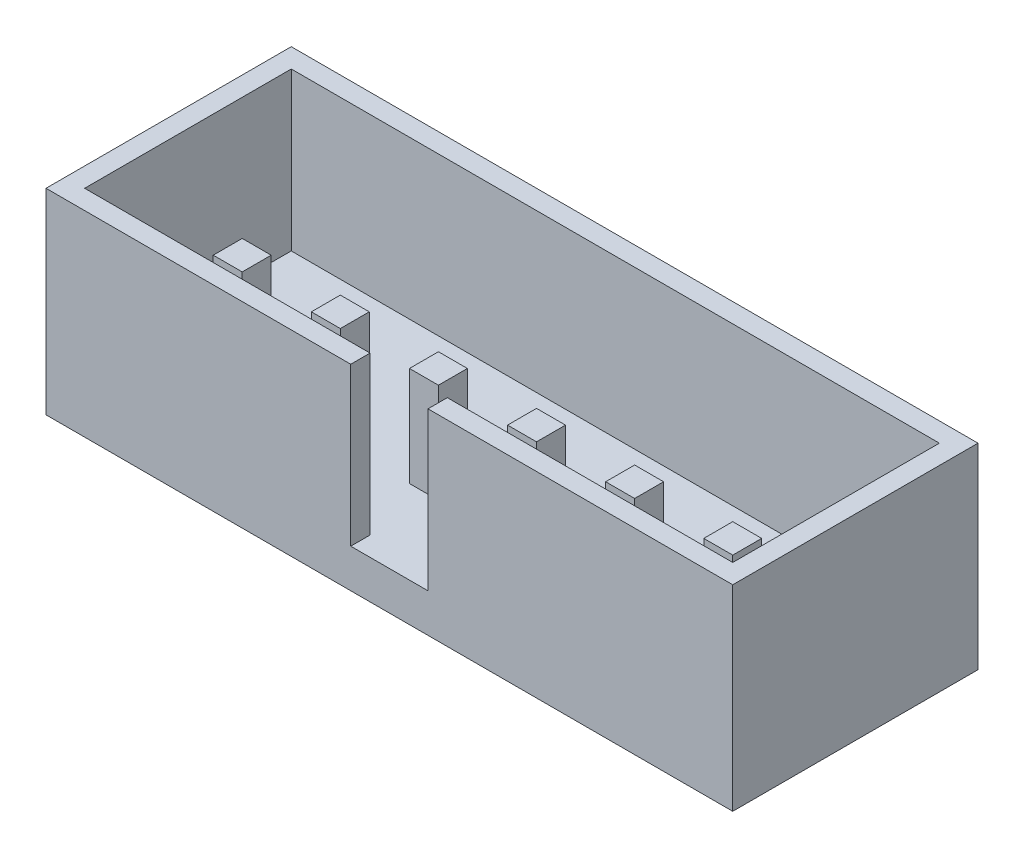
SolidWorks part; units mm, degrees
ref_plane "前视基准面" through (0, 0, 0) normal (0, 0, 1) x (1, 0, 0)
ref_plane "上视基准面" through (0, 0, 0) normal (0, 1, 0) x (1, 0, 0)
ref_plane "右视基准面" through (0, 0, 0) normal (1, 0, 0) x (0, 0, -1)
sketch "草图1" plane through (0, 0, 0) normal (0, 1, 0) x (1, 0, 0)
  line L0 (0, 7.1914) -> (0, -5.4429) construction
  line L1 (-8.89, 3.175) -> (8.89, 3.175)
  line L2 (-8.89, 3.175) -> (-8.89, -3.175)
  line L3 (-8.89, -3.175) -> (8.89, -3.175)
  line L4 (8.89, 3.175) -> (8.89, -3.175)
  line L5 (-10.6234, 0) -> (16.1963, 0) construction
  dimension "D1" = 17.78
  dimension "D2" = 6.35
extrude "拉伸1" add sketch "草图1" along normal blind 5.08
sketch "草图2" plane through (0, 5.08, 0) normal (0, 1, 0) x (-1, 0, 0)
  line L8 (8.39, -2.675) -> (8.39, 2.675)
  line L9 (8.39, 2.675) -> (-8.39, 2.675)
  line L10 (-8.39, 2.675) -> (-8.39, -2.675)
  line L11 (-8.39, -2.675) -> (8.39, -2.675)
  line L12 (8.39, -2.675) -> (8.39, 2.675)
  line L13 (8.39, 2.675) -> (-8.39, 2.675)
  line L14 (-8.39, 2.675) -> (-8.39, -2.675)
  line L15 (-8.39, -2.675) -> (8.39, -2.675)
  dimension "D1" = 0.5
extrude "切除-拉伸1" cut sketch "草图2" against normal offset from surface (4.08 mm away) 1 up to face at (0, 0, 0)
sketch "草图3" plane through (0, 0, 3.175) normal (0, 0, 1) x (1, 0, 0)
  line L0 (-8.89, 5.08) -> (8.89, 5.08) construction
  line L1 (-1, 5.08) -> (1, 5.08)
  line L2 (-1, 5.08) -> (-1, 1)
  line L3 (-1, 1) -> (1, 1)
  line L4 (1, 5.08) -> (1, 1)
  line L5 (8.39, 1) -> (-8.39, 1) construction
  line L6 (0, -1.5083) -> (0, 12.2426) construction
  dimension "D1" = 2
extrude "切除-拉伸2" cut sketch "草图3" against normal blind 1
sketch "草图4" plane through (0, 0, 0) normal (0, -1, 0) x (1, 0, 0)
  line L0 (7.6775, 0.635) -> (-8.5467, 0.635) construction
  line L1 (-8.89, 3.175) -> (8.89, 3.175) construction
  line L2 (0, -3.6953) -> (0, 4.0669) construction
  line L3 (-1.27, 2.1009) -> (-1.27, -0.7012) construction
  line L4 (-1.645, 1.01) -> (-0.895, 1.01)
  line L5 (-1.645, 1.01) -> (-1.645, 0.26)
  line L6 (-1.645, 0.26) -> (-0.895, 0.26)
  line L7 (-0.895, 1.01) -> (-0.895, 0.26)
  line L8 (0.895, 1.01) -> (1.645, 1.01)
  line L9 (0.895, 1.01) -> (0.895, 0.26)
  line L10 (0.895, 0.26) -> (1.645, 0.26)
  line L11 (1.645, 1.01) -> (1.645, 0.26)
  line L12 (2.54, -3.6953) -> (2.54, 4.0669) construction
  line L13 (3.435, 1.01) -> (4.185, 1.01)
  line L14 (3.435, 1.01) -> (3.435, 0.26)
  line L15 (3.435, 0.26) -> (4.185, 0.26)
  line L16 (4.185, 1.01) -> (4.185, 0.26)
  line L17 (5.08, -3.6953) -> (5.08, 4.0669) construction
  line L18 (5.975, 1.01) -> (6.725, 1.01)
  line L19 (5.975, 1.01) -> (5.975, 0.26)
  line L20 (5.975, 0.26) -> (6.725, 0.26)
  line L21 (6.725, 1.01) -> (6.725, 0.26)
  line L22 (7.62, -3.6953) -> (7.62, 4.0669) construction
  line L23 (-4.185, 1.01) -> (-3.435, 1.01)
  line L24 (-4.185, 1.01) -> (-4.185, 0.26)
  line L25 (-4.185, 0.26) -> (-3.435, 0.26)
  line L26 (-3.435, 1.01) -> (-3.435, 0.26)
  line L27 (-3.81, 2.1009) -> (-3.81, -0.7012) construction
  line L28 (5.1375, 0.635) -> (-11.0867, 0.635) construction
  line L29 (-6.725, 1.01) -> (-5.975, 1.01)
  line L30 (-6.725, 1.01) -> (-6.725, 0.26)
  line L31 (-6.725, 0.26) -> (-5.975, 0.26)
  line L32 (-5.975, 1.01) -> (-5.975, 0.26)
  line L33 (-6.35, 2.1009) -> (-6.35, -0.7012) construction
  line L34 (2.5975, 0.635) -> (-13.6267, 0.635) construction
  dimension "D1" = 2.54
  dimension "D2" = 0.75
  dimension "D3" = 0.75
  dimension "D4" = 1.27
  dimension "D5" = 4
  dimension "D6" = 3
extrude "拉伸2" add sketch "草图4" along normal blind 2 and the other way offset from surface (3.58 mm away) 1.5 other way up to face at (0, 5.08, 0.975)
